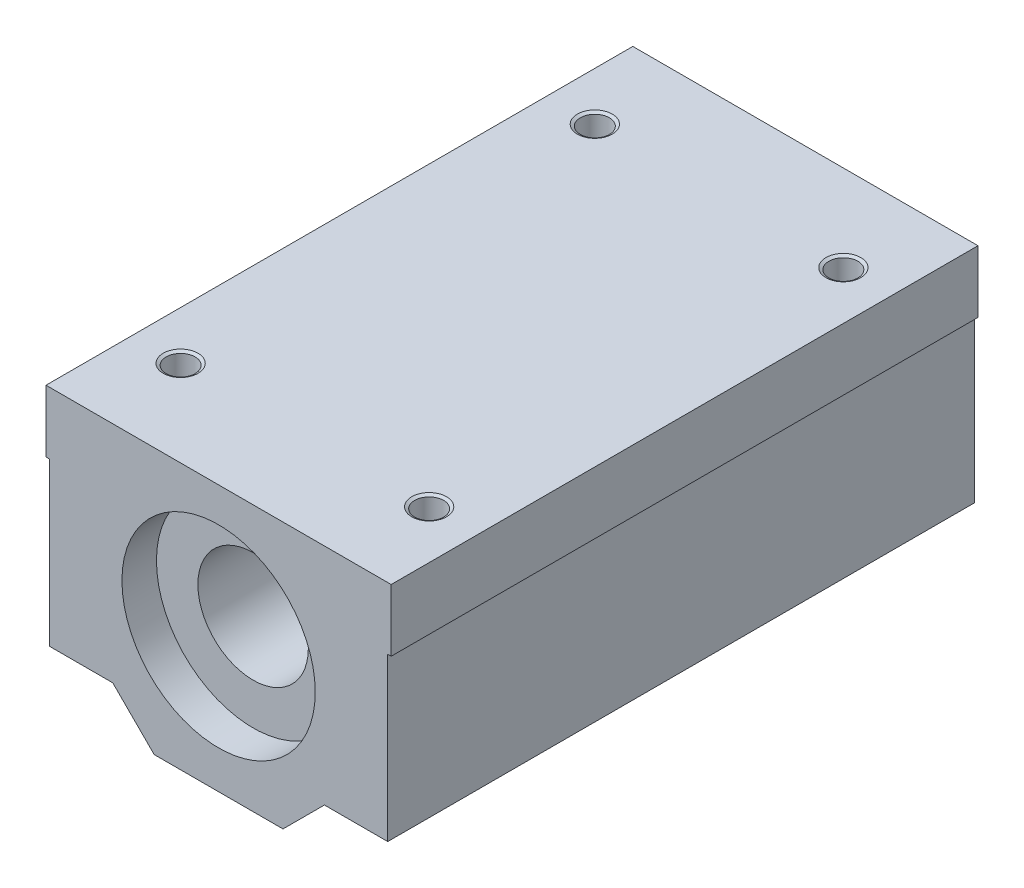
SolidWorks part; units mm, degrees
material "Д16Т ГОСТ 4784-74"
ref_plane "Спереди" through (0, 0, 0) normal (0, 0, 1) x (1, 0, 0)
ref_plane "Сверху" through (0, 0, 0) normal (0, 1, 0) x (1, 0, 0)
ref_plane "Справа" through (0, 0, 0) normal (1, 0, 0) x (0, 0, -1)
sketch "Эскиз1" plane through (0, 0, 0) normal (0, 0, 1) x (1, 0, 0)
  line L0 (0, 0) -> (0, 19) construction
  line L1 (-25, 19) -> (25, 19)
  line L2 (25, 19) -> (25, 10)
  line L3 (25, 10) -> (24.5, 10)
  line L4 (24.5, 10) -> (24.5, -13.5)
  line L5 (24.5, -13.5) -> (15.3296, -13.5)
  line L6 (15.3296, -13.5) -> (9.3296, -19.5)
  line L7 (9.3296, -19.5) -> (-9.3296, -19.5)
  line L8 (-15.3296, -13.5) -> (-9.3296, -19.5)
  line L9 (-24.5, -13.5) -> (-15.3296, -13.5)
  line L10 (-24.5, 10) -> (-24.5, -13.5)
  line L11 (-25, 10) -> (-24.5, 10)
  line L12 (-25, 19) -> (-25, 10)
  circle A0 centre (0, 0) radius 8
  point P12 (0, -19.5)
  dimension "D1" = 25
  dimension "D7" = 16
  dimension "D2" = 9
  dimension "D3" = 0.5
  dimension "D4" = 19
  dimension "D5" = 38.5
  dimension "D6" = 32.5
  dimension "D8" = 135
extrude "Бобышка-Вытянуть1" add sketch "Эскиз1" along normal blind 85
sketch "Эскиз2" plane through (0, 19, 0) normal (0, 1, 0) x (1, 0, 0)
  line L0 (0, 0) -> (0, -85) construction
  line L1 (25, -85) -> (-25, -85) construction
  line L2 (0, -42.5) -> (-25, -42.5) construction
  line L3 (-25, -85) -> (-25, 0) construction
  circle A0 centre (-18, -12.5) radius 1
  circle A1 centre (-18, -72.5) radius 1
  circle A2 centre (18, -72.5) radius 1
  circle A3 centre (18, -12.5) radius 1
  dimension "D1" = 36
  dimension "D2" = 2
  dimension "D3" = 60
extrude "Вырез-Вытянуть1" cut sketch "Эскиз2" against normal through all
hole_wizard "Отверстие обработанное метчиком M51" positions "Эскиз4" profile "Эскиз3" tap size "M5" standard "DIN"
sketch "Эскиз4" plane through (0, 19, 0) normal (0, 1, 0) x (-1, 0, 0)
  point P1 (-18, 12.5)
  point P4 (-18, 72.5)
  point P7 (18, 72.5)
  point P10 (18, 12.5)
sketch "Эскиз3" plane through (18, 19, 12.5) normal (1, 0, 0) x (0, 0, 1)
  line L0 (0, 0) -> (0, 15.2618)
  line L1 (0, 15.2618) -> (2.1, 14)
  line L2 (2.1, 14) -> (2.1, 0.2454)
  line L3 (2.1, 0.2454) -> (2.525, 0)
  line L5 (2.525, 0) -> (0, 0)
  line L6 (-2.1, 0.2454) -> (-2.525, 0) construction
  line L10 (0, 15.2618) -> (-2.1, 14) construction
  line L11 (0, -6.35) -> (0, 107.95) construction
  dimension "Диаметр сверла" = 4.2
  dimension "Глубина сверла" = 14
  dimension "Диаметр передней зенковки" = 5.05
  dimension "Угол передней зенковки" = 120
  dimension "Угол заточки сверла" = 118
cosmetic thread "Отверстие резьбы1" parameters "D1"=10, "D2"=5
cosmetic thread "Отверстие резьбы2" parameters "D1"=10, "D2"=5
cosmetic thread "Отверстие резьбы3" parameters "D1"=10, "D2"=5
cosmetic thread "Отверстие резьбы4" parameters "D1"=10, "D2"=5
sketch "Эскиз6" plane through (0, -13.5, 0) normal (0, -1, 0) x (1, 0, 0)
  circle A0 centre (-18, 72.5) radius 2.15
  circle A1 centre (18, 72.5) radius 2.15
  circle A2 centre (18, 12.5) radius 2.15
  circle A3 centre (-18, 12.5) radius 2.15
  dimension "D1" = 4.3
extrude "Вырез-Вытянуть3" cut sketch "Эскиз6" against normal blind 24
sketch "Эскиз7" plane through (0, 0, 0) normal (0, 0, -1) x (-1, 0, 0)
  circle A0 centre (0, 0) radius 14
  dimension "D1" = 28
extrude "Вырез-Вытянуть4" cut sketch "Эскиз7" against normal blind 5
sketch "Эскиз8" plane through (0, 0, 85) normal (0, 0, 1) x (1, 0, 0)
  circle A0 centre (0, 0) radius 14
  dimension "D1" = 28
extrude "Вырез-Вытянуть5" cut sketch "Эскиз8" against normal blind 5
